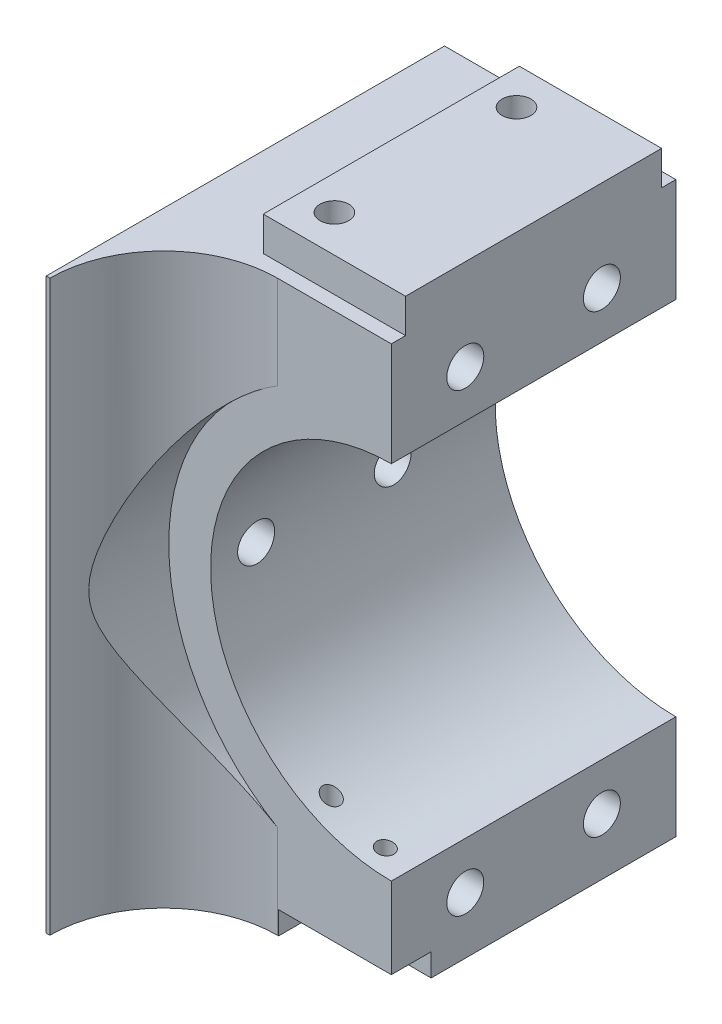
SolidWorks part; units mm, degrees
other "Markup1"
sketch "Sketch12" plane through (-50, 56, -10) normal (-0.1438, 0.9756, -0.1662) x (-0.9889, -0.1353, 0.0611)
ref_plane "Front Plane" through (0, 0, 0) normal (0, 0, 1) x (1, 0, 0)
ref_plane "Top Plane" through (0, 0, 0) normal (0, 1, 0) x (1, 0, 0)
ref_plane "Right Plane" through (0, 0, 0) normal (1, 0, 0) x (0, 0, -1)
sketch "Sketch1" plane through (0, 0, 0) normal (0, 0, 1) x (1, 0, 0)
  circle A2 centre (0, 0) radius 31.75
  circle A4 centre (0, 0) radius 39.1
  circle A5 centre (0, 0) radius 38.1 construction
  dimension "D1" = 1
  dimension "D2" = 63.5
extrude "Centre Hole for L2" add sketch "Sketch1" along normal blind 40 and the other way blind 10 contours A4 | A2
sketch "Sketch2" plane through (0, 0, 40) normal (0, 0, 1) x (1, 0, 0)
  line L0 (0, 48.4974) -> (0, 0) construction
  line L5 (-50, 50) -> (-50, -50)
  line L12 (0, 0) -> (72.986, 0) construction
  line L16 (-50, 50) -> (50, 50)
  line L17 (50, 50) -> (50, -50)
  line L18 (-50, -50) -> (50, -50)
  circle A2 centre (0, 0) radius 39.1
  circle A3 centre (0, 0) radius 39.1 construction
  point P13 (0, 50)
  dimension "D1" = 50
  dimension "D2" = 100
extrude "Main Structure" add sketch "Sketch2" along normal blind 60 and the other way blind 50 contours L5 L18 L17 L16 A2
sketch "Sketch3" plane through (-50, 0, 0) normal (-1, 0, 0) x (0, 0, 1)
  line L0 (100, 50) -> (100, -50) construction
  line L1 (100, 50) -> (100, -50)
  line L2 (-10, 50) -> (100, 50) construction
  line L3 (-10, -50) -> (100, -50) construction
  line L4 (-10, 50) -> (100, 50) construction
  arc A0 (100, 50) -> (100, -50) centre (100, 0) cw
extrude "Bearing Curve" add sketch "Sketch3" against normal blind 10 contours A0 L1
mirror "Upright Mirror" about plane through (0, 0, 0) normal (1, 0, 0) of "Bearing Curve"
sketch "Sketch6" plane through (-50, 0, 0) normal (-1, 0, 0) x (0, 0, 1)
  circle A0 centre (100, 0) radius 10.5
  dimension "D1" = 21
extrude "Shaft Hole" cut sketch "Sketch6" against normal up to surface (10 mm away) up to face at (-40, 0, 125)
sketch "Sketch4" plane through (0, 50, 0) normal (0, 1, 0) x (1, 0, 0)
  line L0 (0, -100) -> (0, 10) construction
  line L3 (-40, -100) -> (-40, -60)
  line L6 (40, -100) -> (40, -60)
  line L7 (-50, 10) -> (50, 10) construction
  line L8 (-40, -100) -> (40, -100) construction
  line L9 (-20, -40) -> (20, -40)
  line L10 (-40, -100) -> (40, -100)
  arc A0 (-40, -60) -> (-20, -40) centre (-20, -60) cw
  arc A1 (40, -60) -> (20, -40) centre (20, -60) ccw
  point P17 (0, -100)
  dimension "D2" = 20
  dimension "D1" = 50
extrude "Wrist Cutout" cut sketch "Sketch4" against normal through all
ref_plane "Plane1" through (0, 0, 0) normal (-1, 0, 0) x (0, 0, 1)
other "SurfaceCut1"
sketch "Sketch11" plane through (0, 50, 0) normal (0, 1, 0) x (1, 0, 0)
  line L0 (0, -40) -> (0, 10) construction
  line L1 (0, -37.5) -> (-25, -37.5)
  line L2 (0, -37.5) -> (0, 7.5)
  line L3 (0, 7.5) -> (-25, 7.5)
  line L4 (-25, -37.5) -> (-25, 7.5)
  line L5 (-50, 10) -> (0, 10) construction
  circle A0 centre (-19, 1) radius 2.525
  circle A1 centre (-19, -31) radius 2.525
  dimension "D4" = 5.05
  dimension "D5" = 19
  dimension "D6" = 6.5
  dimension "D7" = 5.05
  dimension "D8" = 19
  dimension "D1" = 45
  dimension "D2" = 25
  dimension "D3" = 2.5
  dimension "6.5" = 6.5
extrude "Boss-Extrude1" add sketch "Sketch11" along normal blind 6
sketch "Sketch15" plane through (0, -50, 0) normal (0, -1, 0) x (-1, 0, 0)
  line L1 (0, -40) -> (19.8, -40)
  line L2 (0, -40) -> (0, -33)
  line L3 (0, -33) -> (19.8, -33)
  line L4 (19.8, -40) -> (19.8, -33)
  dimension "D1" = 19.8
  dimension "D2" = 7
extrude "Cut-Extrude4" cut sketch "Sketch15" against normal blind 4
sketch "Sketch16" plane through (0, -46, 0) normal (0, -1, 0) x (-1, 0, 0)
  line L0 (19.8, -40) -> (19.8, -33) construction
  line L1 (19.8, -33) -> (0, -33) construction
  line L2 (14.65, -35.9) -> (4.8172, -35.9) construction
  circle A0 centre (14.65, -35.9) radius 1.5
  circle A1 centre (5.15, -35.9) radius 1.5
  point P4 (19.8, -36.5)
  dimension "D1" = 3
  dimension "D2" = 5.15
  dimension "D3" = 2.9
  dimension "D4" = 3
  dimension "D5" = 9.5
extrude "Cut-Extrude5" cut sketch "Sketch16" against normal up to surface (17.8319 mm away)
sketch "Sketch18" plane through (-50, 0, 0) normal (-1, 0, 0) x (0, 0, 1)
  line L2 (-10, 50) -> (-10, -50) construction
  line L4 (-10, 50) -> (100, 50) construction
  circle A0 centre (8, 0) radius 3.25
  circle A1 centre (32, 0) radius 3.25
  dimension "D1" = 6.5
  dimension "D2" = 6.5
  dimension "D3" = 18
  dimension "D4" = 50
  dimension "D6" = 24
extrude "Cut-Extrude6" cut sketch "Sketch18" against normal through all and the other way through all
sketch "Sketch19" plane through (-40, 0, 0) normal (1, 0, 0) x (0, 0, -1)
  line L3 (-60, 50) -> (-100, 50)
  line L4 (-100, -50) -> (-60, -50)
  line L5 (-60, -50) -> (-60, 50)
  line L6 (-60, 50) -> (-100, 50)
  line L7 (-100, -50) -> (-60, -50)
  line L8 (-60, -50) -> (-60, 50)
  arc A1 (-100, 50) -> (-100, -50) centre (-100, 0) ccw
  arc A2 (-100, 50) -> (-100, -50) centre (-100, 0) ccw
  dimension "D1" = 0
extrude "Cut-Extrude7" cut sketch "Sketch19" against normal blind 1.5875
sketch "Sketch9" plane through (-41.5875, 0, 0) normal (1, 0, 0) x (0, 0, -1)
  circle A0 centre (-100, 0) radius 12.05
  dimension "D1" = 24.1
extrude "Bearing" cut sketch "Sketch9" against normal blind 5
sketch "Sketch20" plane through (-50, 0, 0) normal (-1, 0, 0) x (0, 0, 1)
  line L3 (-10, -50) -> (100, -50)
  line L4 (100, 50) -> (-10, 50)
  line L5 (-10, 50) -> (-10, -50)
  line L6 (-10, -50) -> (100, -50)
  line L7 (100, 50) -> (-10, 50)
  line L8 (-10, 50) -> (-10, -50)
  arc A1 (100, -50) -> (100, 50) centre (100, 0) ccw
  arc A2 (100, -50) -> (100, 50) centre (100, 0) ccw
  dimension "D1" = 0
extrude "Cut-Extrude8" cut sketch "Sketch20" against normal blind 3
sketch "Sketch21" plane through (-47, 0, 0) normal (-1, 0, 0) x (0, 0, 1)
  line L0 (3, -40) -> (27, -40) construction
  line L1 (8, 0) -> (8, -40) construction
  line L2 (100, 0) -> (-10, 0) construction
  line L3 (-10, 50) -> (-10, -50) construction
  line L4 (100, 0) -> (150, 0) construction
  circle A2 centre (3, -40) radius 3.25
  circle A3 centre (27, -40) radius 3.25
  circle A4 centre (27, 40) radius 3.25
  circle A5 centre (3, 40) radius 3.25
  arc A6 (100, -50) -> (100, 50) centre (100, 0) ccw construction
  circle A7 centre (125, 0) radius 1.65
  circle A8 centre (32, 0) radius 3.25 construction
  dimension "D1" = 6.5
  dimension "D5" = 3.3
  dimension "D2" = 40
  dimension "D3" = 5
  dimension "D4" = 5
extrude "Cut-Extrude9" cut sketch "Sketch21" against normal through all
sketch "Sketch22" plane through (-47, 0, 0) normal (-1, 0, 0) x (0, 0, 1)
  line L3 (-10, 50) -> (-10, -50)
  line L4 (-10, -50) -> (100, -50)
  line L5 (100, 50) -> (-10, 50)
  line L6 (-10, 50) -> (-10, -50)
  line L7 (-10, -50) -> (100, -50)
  line L8 (100, 50) -> (-10, 50)
  arc A1 (100, -50) -> (100, 50) centre (100, 0) ccw
  arc A2 (100, -50) -> (100, 50) centre (100, 0) ccw
  dimension "D1" = 0
extrude "Cut-Extrude10" cut sketch "Sketch22" against normal blind 6.35
sketch "Sketch23" plane through (0, -50, 0) normal (0, -1, 0) x (-1, 0, 0)
  line L0 (0, -33) -> (0, 10) construction
  line L2 (0, -6.25) -> (40.65, -6.25) construction
  circle A0 centre (15, -7.25) radius 2.275
  point P4 (15, -9.0443)
  dimension "D1" = 4.55
  dimension "D2" = 15
  dimension "D3" = 1
extrude "Cut-Extrude11" cut sketch "Sketch23" against normal blind 6
chamfer "Chamfer1" distance 0.5 angle 45 1 edges at (-15, -50, 4.975)
